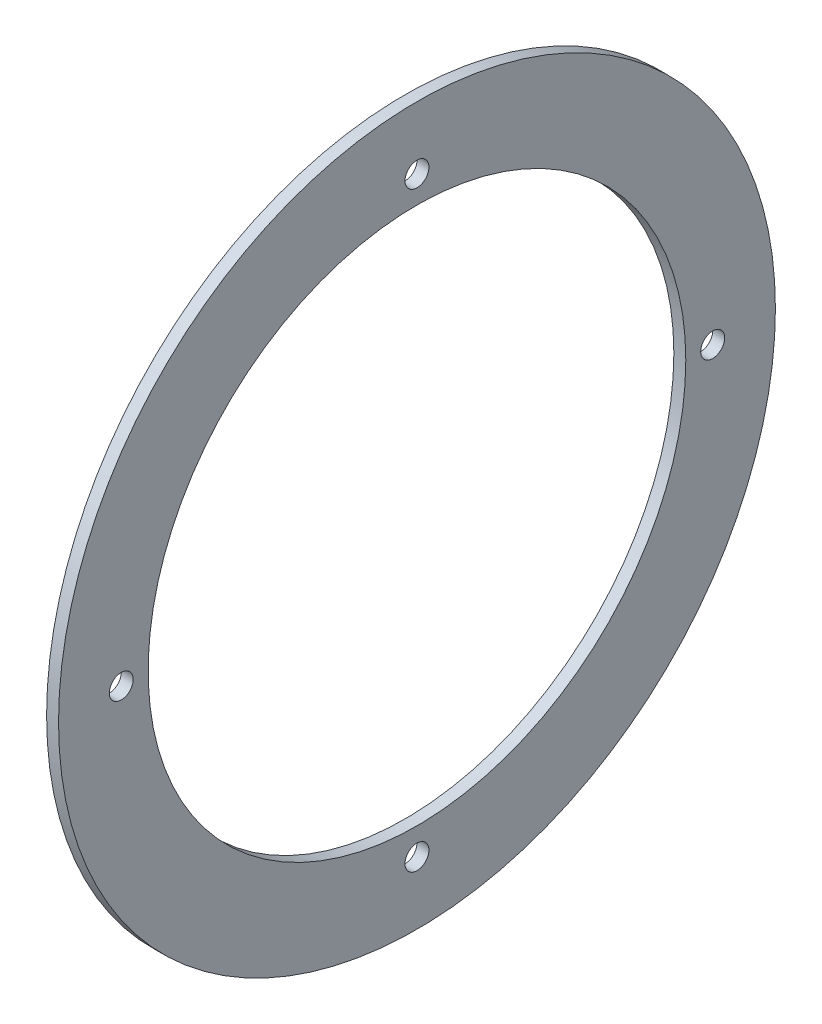
SolidWorks part; units mm, degrees
material "普通碳钢"
ref_plane "前视" through (0, 0, 0) normal (0, 0, 1) x (1, 0, 0)
ref_plane "上视" through (0, 0, 0) normal (0, 1, 0) x (1, 0, 0)
ref_plane "右视" through (0, 0, 0) normal (1, 0, 0) x (0, 0, -1)
sketch "草图1" plane through (0, 0, 0) normal (1, 0, 0) x (0, 0, -1)
  circle A0 centre (0, 0) radius 45
  circle A1 centre (0, 0) radius 60
  circle A2 centre (0, 0) radius 49.4975 construction
  circle A3 centre (0, 49.4975) radius 2
  circle A4 centre (-49.4975, 0) radius 2
  circle A5 centre (0, -49.4975) radius 2
  circle A6 centre (49.4975, 0) radius 2
  dimension "D1" = 120
  dimension "D2" = 90
  dimension "D3" = 70
  dimension "D4" = 4
extrude "凸台-拉伸1" add sketch "草图1" along normal blind 2
